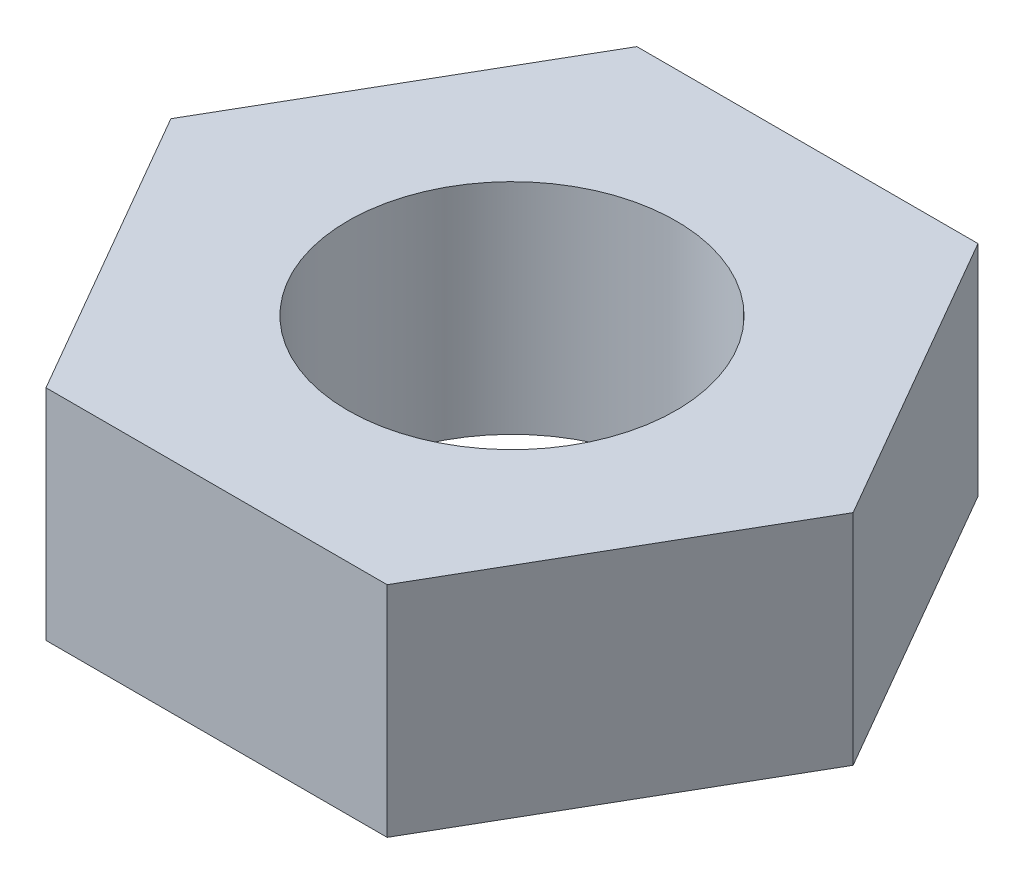
SolidWorks part; units mm, degrees
material "AISI 347 Annealed Stainless Steel (SS)"
ref_plane "Front Plane" through (0, 0, 0) normal (0, 0, 1) x (1, 0, 0)
ref_plane "Top Plane" through (0, 0, 0) normal (0, 1, 0) x (1, 0, 0)
ref_plane "Right Plane" through (0, 0, 0) normal (1, 0, 0) x (0, 0, -1)
sketch "Sketch1" plane through (0, 0, 0) normal (0, 1, 0) x (1, 0, 0)
  line L1 (-3.1177, 0) -> (-1.5588, -2.7)
  line L2 (-1.5588, -2.7) -> (1.5588, -2.7)
  line L3 (1.5588, -2.7) -> (3.1177, 0)
  line L4 (3.1177, 0) -> (1.5588, 2.7)
  line L5 (1.5588, 2.7) -> (-1.5588, 2.7)
  line L6 (-1.5588, 2.7) -> (-3.1177, 0)
  circle A0 centre (0, 0) radius 2.7 construction
  circle A1 centre (0, 0) radius 1.5
  dimension "D1" = 3
  dimension "D2" = 5.4
extrude "Boss-Extrude1" add sketch "Sketch1" along normal blind 2
